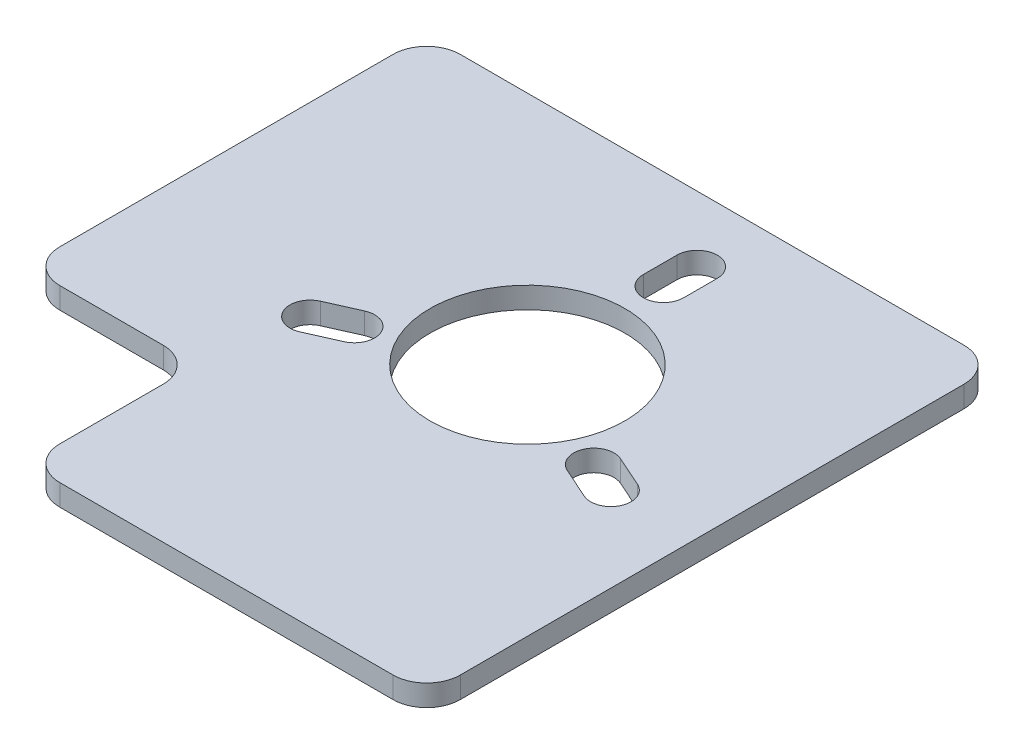
SolidWorks part; units mm, degrees
ref_plane "Front Plane" through (0, 0, 0) normal (0, 0, 1) x (1, 0, 0)
ref_plane "Top Plane" through (0, 0, 0) normal (0, 1, 0) x (1, 0, 0)
ref_plane "Right Plane" through (0, 0, 0) normal (1, 0, 0) x (0, 0, -1)
sketch "Sketch1" plane through (0, 0, 0) normal (0, 1, 0) x (1, 0, 0)
  line L1 (0, 0) -> (170, 0)
  line L2 (0, 0) -> (0, 170)
  line L3 (0, 170) -> (170, 170)
  line L4 (170, 0) -> (170, 170)
  circle A0 centre (100, 100) radius 29
  dimension "D3" = 58
  dimension "D4" = 70
  dimension "D5" = 70
  dimension "D1" = 170
  dimension "D2" = 170
extrude "Boss-Extrude1" add sketch "Sketch1" along normal blind 6.35
sketch "Sketch2" plane through (0, 6.35, 0) normal (0, 1, 0) x (1, 0, 0)
  line L1 (0, 0) -> (50.8, 0)
  line L2 (0, 0) -> (0, 50.8)
  line L3 (0, 50.8) -> (50.8, 50.8)
  line L4 (50.8, 0) -> (50.8, 50.8)
  dimension "D1" = 50.8
  dimension "D2" = 50.8
extrude "Cut-Extrude1" cut sketch "Sketch2" against normal through all
fillet "Fillet1" radius 10 6 edges at (170, 3.175, -170) (170, 3.175, 0) (0, 3.175, -170) (50.8, 3.175, -50.8) (50.8, 3.175, 0) (0, 3.175, -50.8)
sketch "Sketch3" plane through (0, 6.35, 0) normal (0, 1, 0) x (1, 0, 0)
  line L0 (100, 100) -> (100, 150.5) construction
  line L1 (100, 100) -> (55.2363, 80.0699) construction
  line L2 (100, 100) -> (144.7637, 80.0699) construction
  line L4 (160, 170) -> (10, 170) construction
  line L7 (100, 150.5) -> (100, 140.5) construction
  line L10 (106, 150.5) -> (106, 140.5)
  line L15 (94, 150.5) -> (94, 140.5)
  line L16 (55.2363, 80.0699) -> (64.3717, 84.1373) construction
  line L17 (52.7959, 85.5512) -> (61.9313, 89.6185)
  line L18 (57.6767, 74.5886) -> (66.8121, 78.656)
  line L19 (144.7637, 80.0699) -> (135.6283, 84.1373) construction
  line L20 (142.3233, 74.5886) -> (133.1879, 78.656)
  line L21 (147.2041, 85.5512) -> (138.0687, 89.6185)
  arc A7 (106, 150.5) -> (94, 150.5) centre (100, 150.5) ccw
  arc A8 (94, 140.5) -> (106, 140.5) centre (100, 140.5) ccw
  arc A9 (52.7959, 85.5512) -> (57.6767, 74.5886) centre (55.2363, 80.0699) ccw
  arc A10 (66.8121, 78.656) -> (61.9313, 89.6185) centre (64.3717, 84.1373) ccw
  arc A11 (142.3233, 74.5886) -> (147.2041, 85.5512) centre (144.7637, 80.0699) ccw
  arc A12 (138.0687, 89.6185) -> (133.1879, 78.656) centre (135.6283, 84.1373) ccw
  point P6 (100, 145.5)
  point P12 (59.804, 82.1036)
  point P18 (140.196, 82.1036)
  dimension "D4" = 10
  dimension "D5" = 6
  dimension "D1" = 50.5
  dimension "D2" = 24
  dimension "D3" = 24
  dimension "D6" = 49
extrude "Cut-Extrude2" cut sketch "Sketch3" against normal through all
